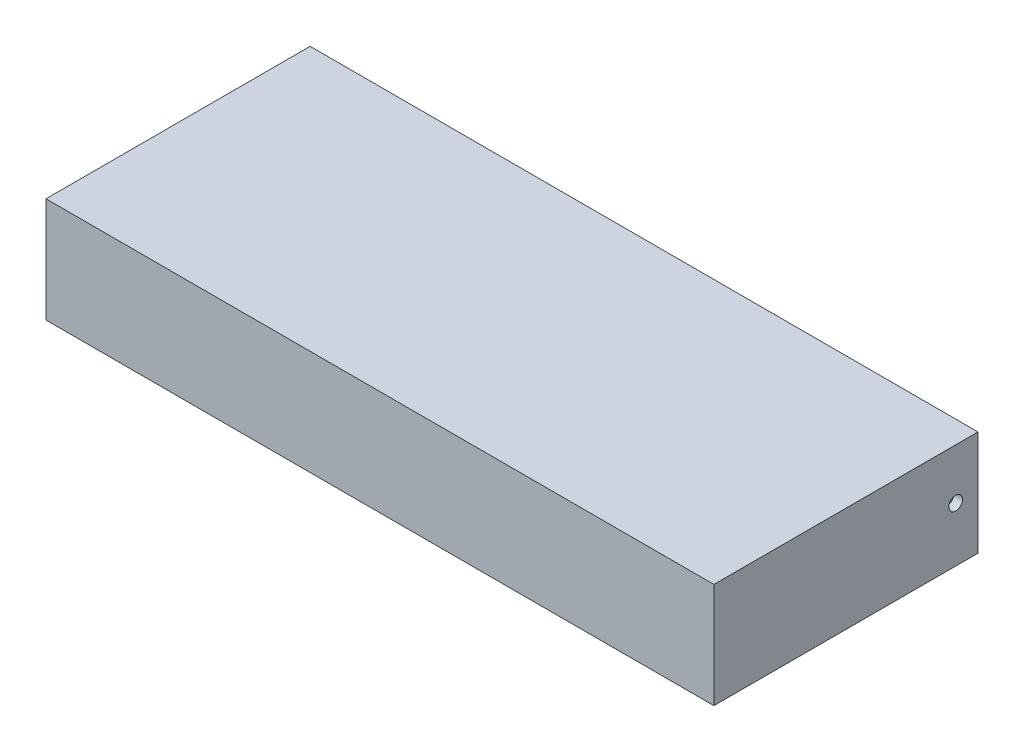
SolidWorks part; units mm, degrees
ref_plane "정면" through (0, 0, 0) normal (0, 0, 1) x (1, 0, 0)
ref_plane "윗면" through (0, 0, 0) normal (0, 1, 0) x (1, 0, 0)
ref_plane "우측면" through (0, 0, 0) normal (1, 0, 0) x (0, 0, -1)
sketch "스케치1" plane through (0, 0, 0) normal (0, 1, 0) x (1, 0, 0)
  line L1 (760, 300.5) -> (-760, 300.5)
  line L2 (760, 300.5) -> (760, -300.5)
  line L3 (760, -300.5) -> (-760, -300.5)
  line L4 (-760, 300.5) -> (-760, -300.5)
  line L5 (760, 300.5) -> (-760, -300.5) construction
  line L6 (760, -300.5) -> (-760, 300.5) construction
  point P0 (0, 0)
extrude "보스-돌출1" add sketch "스케치1" along normal blind 239
sketch "스케치2" plane through (760, 0, 0) normal (1, 0, 0) x (0, 0, -1)
  line L0 (300.5, 239) -> (300.5, 0) construction
  line L1 (334.7358, 0) -> (-334.7358, 0) construction
  circle A0 centre (249.7, 124) radius 15.6
  dimension "D1" = 50.8
  dimension "D2" = 124
extrude "컷-돌출1" cut sketch "스케치2" against normal blind 20
